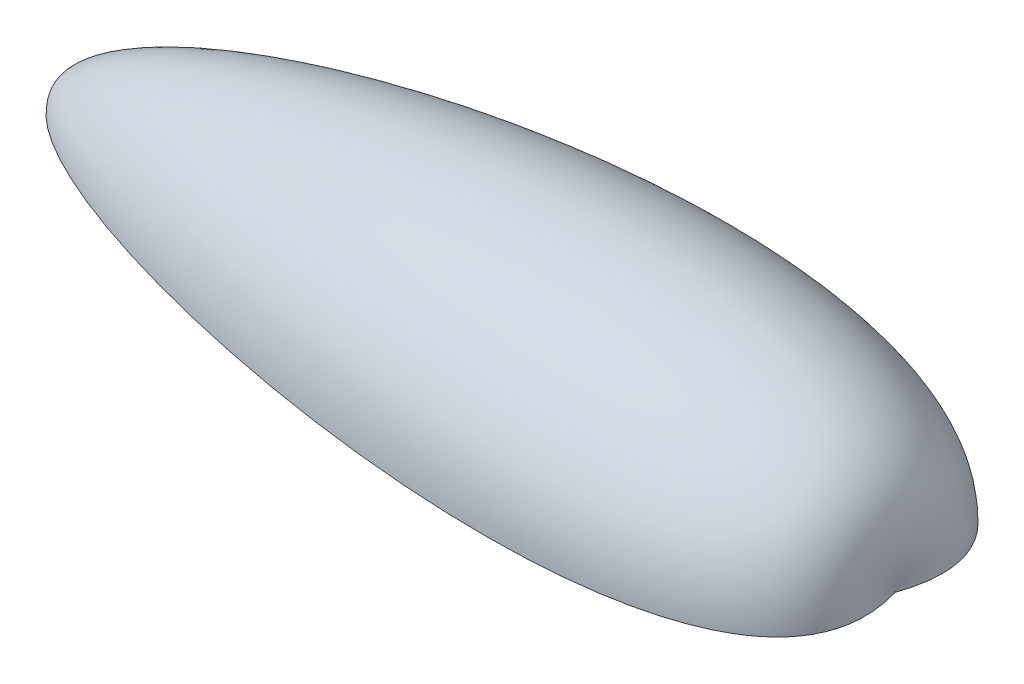
SolidWorks part; units mm, degrees
ref_plane "Front" through (0, 0, 0) normal (0, 0, 1) x (1, 0, 0)
ref_plane "Top" through (0, 0, 0) normal (0, 1, 0) x (1, 0, 0)
ref_plane "Right" through (0, 0, 0) normal (1, 0, 0) x (0, 0, -1)
sketch "Sketch2" plane through (0, 0, 0) normal (0, 1, 0) x (1, 0, 0)
  line L0 (-62.0775, -3.4567) -> (39.5225, -5.7535)
  spline S0 degree 3 poles (-62.0775, -3.4567) (-61.5949, 11.6749) (51.3687, 28.5059) (39.5225, -5.7535) knots 0 0 0 0 1 1 1 1
  dimension "D1" = 101.6
revolve "Revolve1" add sketch "Sketch2" angle 180 about L0
